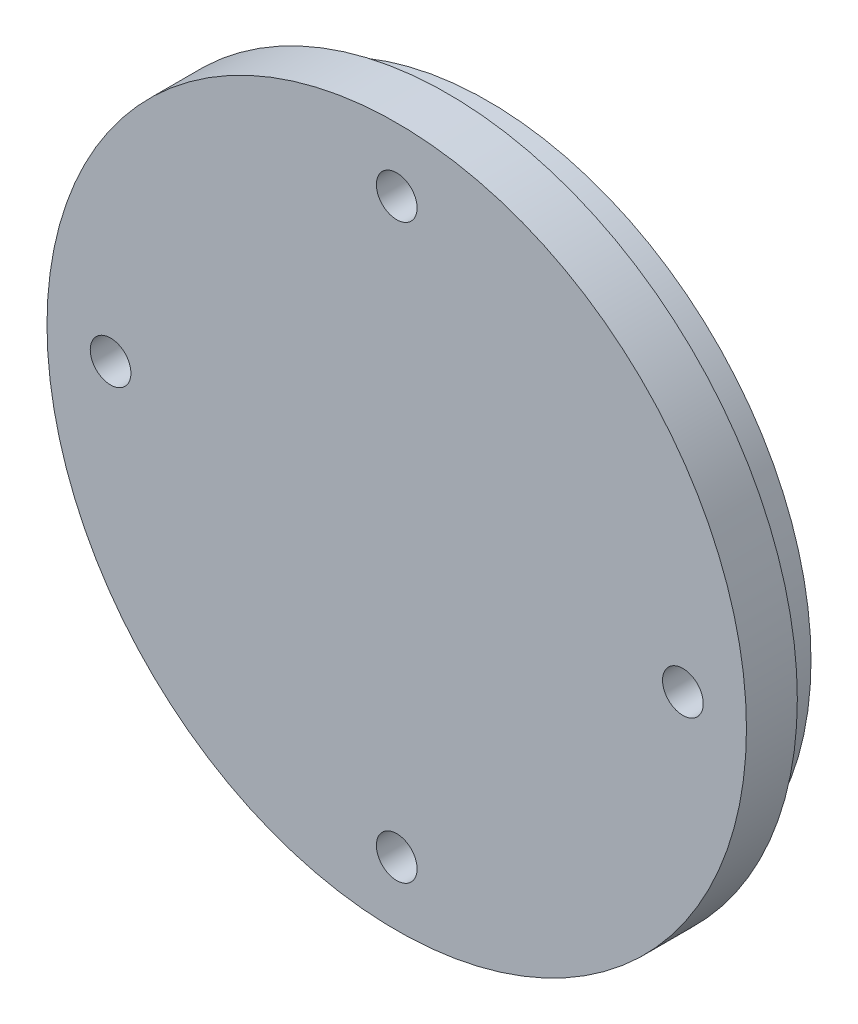
SolidWorks part; units mm, degrees
material "ABS"
ref_plane "正面" through (0, 0, 0) normal (0, 0, 1) x (1, 0, 0)
ref_plane "平面" through (0, 0, 0) normal (0, 1, 0) x (1, 0, 0)
ref_plane "右側面" through (0, 0, 0) normal (1, 0, 0) x (0, 0, -1)
sketch "ｽｹｯﾁ1" plane through (0, 0, 0) normal (0, 0, 1) x (1, 0, 0)
  circle A0 centre (0, 0) radius 27.5
  dimension "D1" = 55
extrude "ﾎﾞｽ - 押し出し1" add sketch "ｽｹｯﾁ1" along normal blind 4
sketch "ｽｹｯﾁ2" plane through (0, 0, 0) normal (0, 0, -1) x (-1, 0, 0)
  circle A0 centre (0, 0) radius 25.4
  dimension "D1" = 50.8
extrude "ﾎﾞｽ - 押し出し2" add sketch "ｽｹｯﾁ2" along normal blind 3.175
sketch "ｽｹｯﾁ3" plane through (0, 0, -3.175) normal (0, 0, -1) x (-1, 0, 0)
  circle A0 centre (0, 0) radius 22.5 construction
  circle A1 centre (0, 22.5) radius 1.6
  circle A2 centre (22.5, 0) radius 1.6
  circle A3 centre (0, -22.5) radius 1.6
  circle A4 centre (-22.5, 0) radius 1.6
  point P14 (0, 0)
  dimension "D1" = 45
  dimension "D2" = 3.2
  dimension "D3" = 4
extrude "ｶｯﾄ - 押し出し1" cut sketch "ｽｹｯﾁ3" against normal through all
